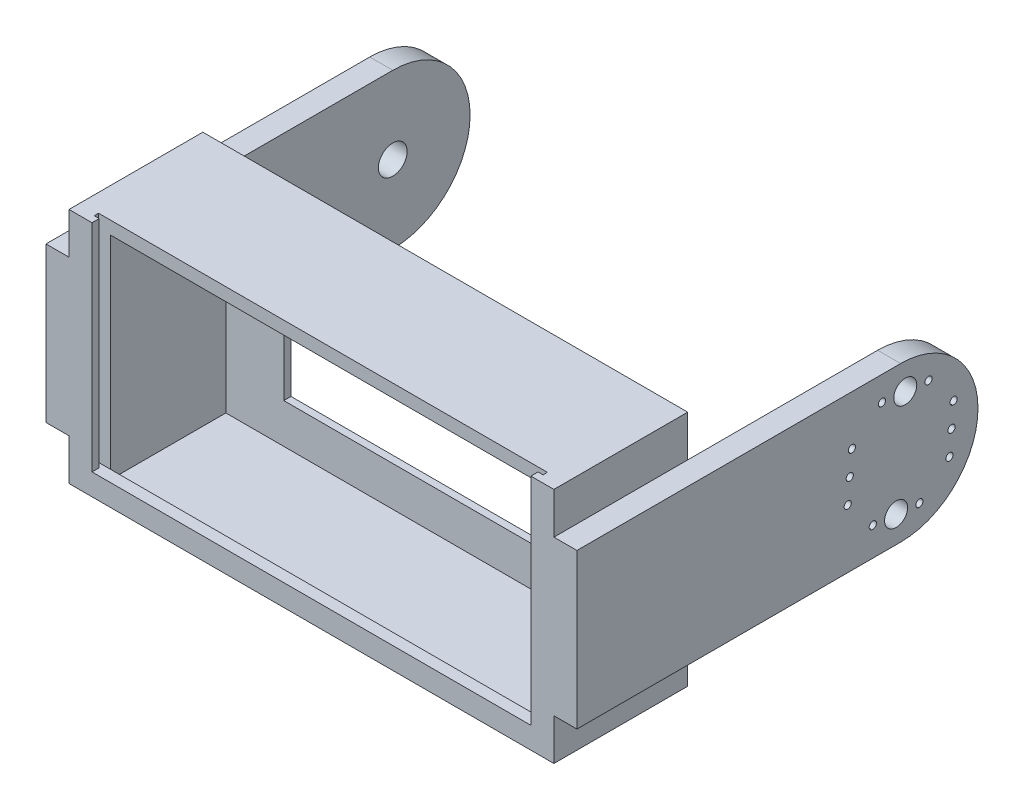
SolidWorks part; units mm, degrees
ref_plane "정면" through (0, 0, 0) normal (0, 0, 1) x (1, 0, 0)
ref_plane "윗면" through (0, 0, 0) normal (0, 1, 0) x (1, 0, 0)
ref_plane "우측면" through (0, 0, 0) normal (1, 0, 0) x (0, 0, -1)
ref_plane "평면4" through (62.3829, 0, 0) normal (1, 0, 0) x (0, 0, -1)
sketch "스케치2" plane through (62.3829, 0, 0) normal (1, 0, 0) x (0, 0, -1)
  line L0 (-65.6774, 80.4181) -> (-110.6774, 80.4181)
  line L1 (-110.6774, 80.4181) -> (-110.6774, 58.9181)
  line L2 (-110.6774, 58.9181) -> (-65.6774, 58.9181)
  circle A0 centre (-61.8032, 76.4477) radius 0.5 construction
  circle A1 centre (-65.6774, 69.6681) radius 10.75
  arc A2 (-65.6774, 58.9181) -> (-65.6774, 80.4181) centre (-65.6774, 69.6681) ccw
  circle A3 centre (-66.3147, 62.5968) radius 1.6
  circle A4 centre (-68.277, 77.0312) radius 0.5 construction
  circle A5 centre (-72.457, 73.5423) radius 0.5 construction
  circle A6 centre (-72.7488, 70.3054) radius 0.5 construction
  circle A7 centre (-73.0405, 67.0685) radius 0.5 construction
  circle A8 centre (-69.5516, 62.8885) radius 0.5 construction
  circle A10 centre (-63.0778, 62.305) radius 0.5 construction
  circle A11 centre (-58.8978, 65.7939) radius 0.5 construction
  circle A12 centre (-58.6061, 69.0308) radius 0.5 construction
  circle A13 centre (-58.3144, 72.2677) radius 0.5 construction
  circle A14 centre (-61.8032, 76.4477) radius 0.5
  circle A16 centre (-68.277, 77.0312) radius 0.5
  circle A17 centre (-72.457, 73.5423) radius 0.5
  circle A18 centre (-72.7488, 70.3054) radius 0.5
  circle A19 centre (-73.0405, 67.0685) radius 0.5
  circle A20 centre (-69.5516, 62.8885) radius 0.5
  circle A22 centre (-63.0778, 62.305) radius 0.5
  circle A23 centre (-58.8978, 65.7939) radius 0.5
  circle A24 centre (-58.6061, 69.0308) radius 0.5
  circle A25 centre (-58.3144, 72.2677) radius 0.5
  circle A26 centre (-65.0401, 76.7394) radius 1.6
  dimension "D3" = 3.2
  dimension "D2" = 45
  dimension "D1" = 0
extrude "Boss-Extrude1" add sketch "스케치2" along normal blind 3.2
sketch "Sketch1" plane through (62.3829, 0, 0) normal (-1, 0, 0) x (0, 0, 1)
  line L1 (110.6774, 86.1681) -> (92.0774, 86.1681)
  line L2 (110.6774, 86.1681) -> (110.6774, 53.1681)
  line L3 (110.6774, 53.1681) -> (92.0774, 53.1681)
  line L4 (92.0774, 86.1681) -> (92.0774, 53.1681)
  line L5 (110.6774, 80.4181) -> (110.6774, 58.9181) construction
  line L7 (109.0774, 84.3681) -> (93.0774, 84.3681)
  line L8 (109.0774, 84.3681) -> (109.0774, 54.9681)
  line L9 (109.0774, 54.9681) -> (93.0774, 54.9681)
  line L10 (93.0774, 84.3681) -> (93.0774, 54.9681)
  point P7 (110.6774, 69.6681)
  dimension "D1" = 33
  dimension "D2" = 1.6
  dimension "D3" = 1.8
  dimension "D4" = 1.8
  dimension "D5" = 1
  dimension "D6" = 16
extrude "Boss-Extrude2" add sketch "Sketch1" along normal blind 67.4
sketch "Sketch2" plane through (0, 0, 92.0774) normal (0, 0, -1) x (-1, 0, 0)
  line L0 (-28.6829, 86.1681) -> (-28.6829, 53.1681) construction
  line L1 (5.0171, 86.1681) -> (-62.3829, 86.1681) construction
  line L2 (5.0171, 53.1681) -> (-62.3829, 53.1681) construction
  line L3 (-28.6829, 69.6681) -> (5.0171, 69.6681) construction
  line L4 (5.0171, 86.1681) -> (5.0171, 53.1681) construction
  line L6 (-50.1313, 78.8516) -> (-7.2344, 78.8516)
  line L7 (-50.1313, 78.8516) -> (-50.1313, 60.4846)
  line L8 (-50.1313, 60.4846) -> (-7.2344, 60.4846)
  line L9 (-7.2344, 78.8516) -> (-7.2344, 60.4846)
  line L10 (-50.1313, 78.8516) -> (-7.2344, 60.4846) construction
  line L11 (-50.1313, 60.4846) -> (-7.2344, 78.8516) construction
extrude "Cut-Extrude1" cut sketch "Sketch2" against normal up to next
sketch "Sketch3" plane through (0, 0, 110.6774) normal (0, 0, 1) x (1, 0, 0)
  line L0 (-5.0171, 86.1681) -> (62.3829, 86.1681) construction
  line L1 (15.1829, 78.1681) -> (42.1829, 78.1681)
  line L2 (15.1829, 78.1681) -> (15.1829, 61.1681)
  line L3 (15.1829, 61.1681) -> (42.1829, 61.1681)
  line L4 (42.1829, 78.1681) -> (42.1829, 61.1681)
  line L6 (-5.0171, 86.1681) -> (62.3829, 53.1681) construction
  line L7 (62.3829, 86.1681) -> (-5.0171, 53.1681) construction
  line L8 (15.1829, 78.1681) -> (42.1829, 61.1681) construction
  line L9 (42.1829, 78.1681) -> (15.1829, 61.1681) construction
  point P6 (28.6829, 69.6681)
  point P16 (28.6829, 69.6681)
  dimension "D1" = 8
  dimension "D2" = 17
  dimension "D3" = 0
  dimension "D4" = 27
extrude "Cut-Extrude2" cut sketch "Sketch3" against normal up to next
sketch "Sketch4" plane through (-5.0171, 0, 0) normal (-1, 0, 0) x (0, 0, 1)
  line L0 (65.6774, 80.4181) -> (110.6774, 80.4181) construction
  line L1 (110.6774, 58.9181) -> (65.6774, 58.9181) construction
  line L2 (65.6774, 80.4181) -> (110.6774, 80.4181)
  line L3 (110.6774, 58.9181) -> (65.6774, 58.9181)
  line L4 (110.6774, 80.4181) -> (110.6774, 58.9181)
  arc A0 (65.6774, 80.4181) -> (65.6774, 58.9181) centre (65.6774, 69.6681) ccw construction
  arc A1 (65.6774, 80.4181) -> (65.6774, 58.9181) centre (65.6774, 69.6681) ccw
extrude "Boss-Extrude3" add sketch "Sketch4" along normal blind 3.2
sketch "Sketch5" plane through (-8.2171, 0, 0) normal (-1, 0, 0) x (0, 0, 1)
  line L0 (54.9274, 69.6681) -> (65.6774, 69.6681) construction
  arc A0 (65.6774, 80.4181) -> (65.6774, 58.9181) centre (65.6774, 69.6681) ccw construction
  circle A1 centre (65.6774, 69.6681) radius 2
  dimension "D1" = 4
sketch "Sketch6" plane through (62.3829, 0, 0) normal (1, 0, 0) x (0, 0, -1)
  line L1 (-109.0774, 84.3681) -> (-93.0774, 84.3681)
  line L2 (-109.0774, 84.3681) -> (-109.0774, 54.9681)
  line L3 (-109.0774, 54.9681) -> (-93.0774, 54.9681)
  line L4 (-93.0774, 84.3681) -> (-93.0774, 54.9681)
extrude "Cut-Extrude3" cut sketch "Sketch5" against normal blind 10 contours A1
extrude "Boss-Extrude4" add sketch "Sketch6" against normal blind 4.2
sketch "Sketch7" plane through (-5.0171, 0, 0) normal (-1, 0, 0) x (0, 0, 1)
  line L1 (93.0774, 84.3681) -> (109.0774, 84.3681)
  line L2 (93.0774, 84.3681) -> (93.0774, 54.9681)
  line L3 (93.0774, 54.9681) -> (109.0774, 54.9681)
  line L4 (109.0774, 84.3681) -> (109.0774, 54.9681)
extrude "Boss-Extrude5" add sketch "Sketch7" against normal blind 4.2
sketch "Sketch10" plane through (0, 86.1681, 0) normal (0, 1, 0) x (1, 0, 0)
  line L1 (-1.8171, -110.6774) -> (59.1829, -110.6774)
  line L2 (-2.5171, -109.6774) -> (-2.5171, -109.0774)
  line L3 (-2.5171, -109.0774) -> (59.8829, -109.0774)
  line L4 (59.8829, -109.6774) -> (59.8829, -109.0774)
  line L5 (-2.5171, -109.6774) -> (-1.8171, -109.6774)
  line L6 (-1.8171, -109.6774) -> (-1.8171, -110.6774)
  line L7 (59.8829, -109.6774) -> (59.1829, -109.6774)
  line L8 (59.1829, -109.6774) -> (59.1829, -110.6774)
  line L9 (-5.0171, -110.6774) -> (-5.0171, -92.0774) construction
  line L10 (62.3829, -92.0774) -> (62.3829, -110.6774) construction
  line L11 (-5.0171, -110.6774) -> (62.3829, -110.6774) construction
  dimension "D1" = 2.5
  dimension "D2" = 2.5
  dimension "D3" = 0.7
  dimension "D4" = 0.7
  dimension "D5" = 0.6
  dimension "D6" = 1
  dimension "D7" = 0
extrude "Cut-Extrude5" cut sketch "Sketch10" against normal blind 30
